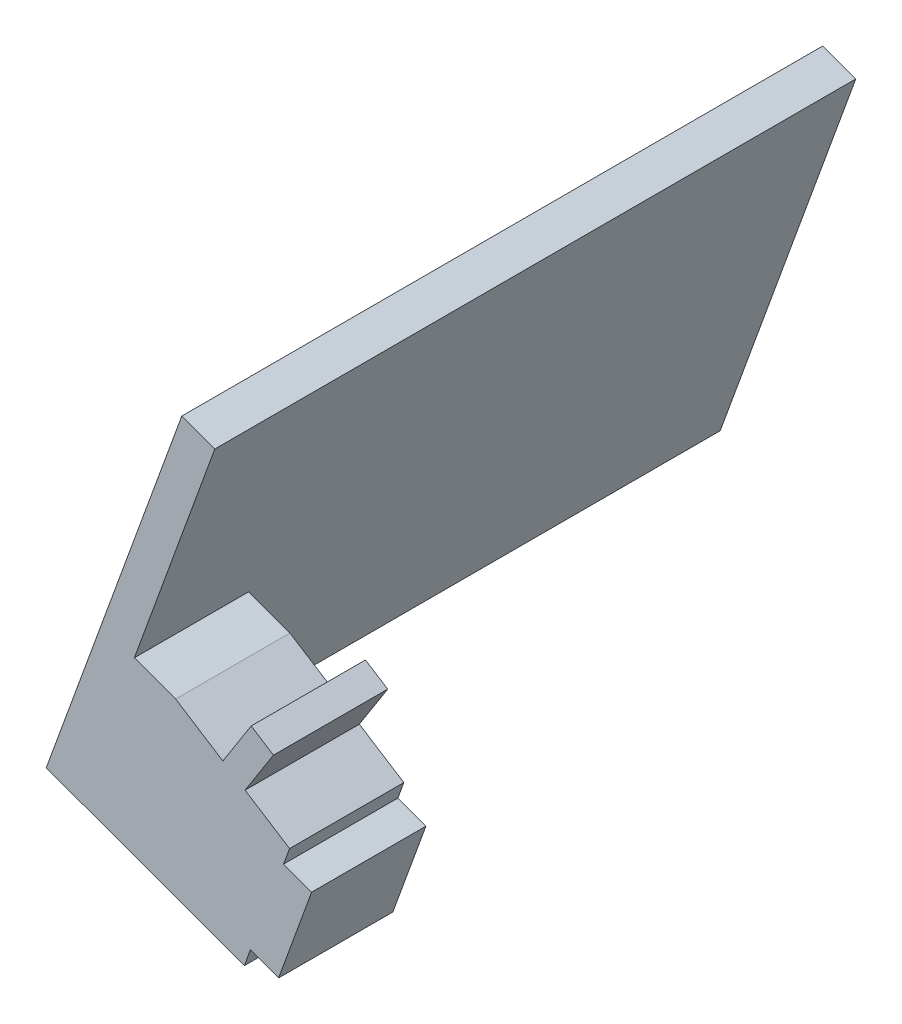
SolidWorks part; units mm, degrees
ref_plane "Plane1" through (0, 0, 0) normal (0, 0, 1) x (1, 0, 0)
ref_plane "Plane2" through (0, 0, 0) normal (0, 1, 0) x (1, 0, 0)
ref_plane "Plane3" through (0, 0, 0) normal (1, 0, 0) x (0, 0, -1)
sketch "Sketch1" plane through (0, 0, 0) normal (0, 0, 1) x (1, 0, 0)
  line L1 (0, 0) -> (203.2, 0)
  line L2 (0, 0) -> (0, 101.6)
  line L3 (0, 101.6) -> (203.2, 101.6)
  line L4 (203.2, 0) -> (203.2, 101.6)
  dimension "D1" = 203.2
  dimension "D2" = 101.6
extrude "Extrude1" add sketch "Sketch1" along normal blind 50.8
sketch "Sketch2" plane through (0, 0, 50.8) normal (0, 0, 1) x (1, 0, 0)
  line L0 (83.0232, 99.06) -> (89.3732, 99.06)
  line L2 (157.48, 83.82) -> (157.48, 78.74)
  line L3 (157.48, 78.74) -> (91.44, 78.74)
  line L4 (91.44, 78.74) -> (83.0232, 99.06)
  line L5 (203.2, 101.6) -> (0, 101.6) construction
  line L6 (0, 101.6) -> (0, 0) construction
  line L7 (157.48, 83.82) -> (102.4931, 88.7077)
  line L8 (98.7377, 90.3765) -> (89.3732, 99.06)
  arc A0 (98.7377, 90.3765) -> (102.4931, 88.7077) centre (103.0553, 95.0328) ccw
  point P12 (100.33, 88.9)
  dimension "D10" = 6.35
  dimension "D1" = 67.5
  dimension "D2" = 20.32
  dimension "D3" = 2.54
  dimension "D4" = 5.08
  dimension "D5" = 66.04
  dimension "D6" = 157.48
  dimension "D7" = 6.35
  dimension "D8" = 57.15
  dimension "D9" = 5.08
sketch "Sketch4" plane through (0, 0, 50.8) normal (0, 0, 1) x (1, 0, 0)
  line L0 (86.5799, 90.4733) -> (72.5, 84.6412)
  line L1 (91.44, 78.74) -> (83.0232, 99.06) construction
  line L2 (72.5, 84.6412) -> (69.6673, 84.8425)
  line L3 (69.6673, 84.8425) -> (73.0694, 76.6292)
  line L4 (73.0694, 76.6292) -> (74.93, 78.7745)
  line L5 (74.93, 78.7745) -> (89.01, 84.6066)
  line L6 (89.01, 84.6066) -> (91.8426, 84.4053)
  line L7 (91.8426, 84.4053) -> (88.4406, 92.6186)
  line L8 (88.4406, 92.6186) -> (86.5799, 90.4733)
  line L9 (79.54, 87.5572) -> (81.97, 81.6906)
  dimension "D1" = 6.35
  dimension "D2" = 8.89
  dimension "D3" = 1.27
  dimension "D4" = 8.89
  dimension "D5" = 1.27
  dimension "D6" = 2.54
  dimension "D7" = 2.54
  dimension "D8" = 15.24
  dimension "D9" = 6.35
sketch "Sketch5" plane through (0, 0, 50.8) normal (0, 0, 1) x (1, 0, 0)
  line L0 (69.7842, 91.1978) -> (77.5603, 72.4245)
  line L1 (77.5603, 72.4245) -> (43.4353, 38.2996)
  line L2 (43.4353, 38.2996) -> (23.4233, 51.0486)
  line L5 (23.4233, 51.0486) -> (30.1436, 56.8684)
  line L6 (157.48, 78.74) -> (91.44, 78.74) construction
  line L7 (30.1436, 56.8684) -> (37.6275, 52.1007)
  line L8 (45.5295, 52.9661) -> (64.4212, 71.8578)
  line L9 (65.7977, 78.778) -> (63.0639, 85.3779)
  line L10 (63.0639, 85.3779) -> (69.7842, 91.1978)
  arc A0 (37.6275, 52.1007) -> (45.5295, 52.9661) centre (41.0393, 57.4562) ccw
  arc A1 (65.7977, 78.778) -> (64.4212, 71.8578) centre (59.9311, 76.3479) cw
  point P14 (41.9258, 49.3624)
  dimension "D10" = 6.35
  dimension "D1" = 135
  dimension "D2" = 6.35
  dimension "D3" = 8.89
  dimension "D4" = 48.26
  dimension "D5" = 102.5
  dimension "D6" = 8.89
  dimension "D7" = 20.32
  dimension "D8" = 8.89
  dimension "D9" = 13.97
sketch "Sketch6" plane through (0, 0, 50.8) normal (0, 0, 1) x (1, 0, 0)
  line L0 (31.6531, 45.8056) -> (23.4647, 32.9524)
  line L1 (43.4353, 38.2996) -> (23.4233, 51.0486) construction
  line L2 (23.4647, 32.9524) -> (21.0288, 31.4925)
  line L3 (21.0288, 31.4925) -> (26.3844, 28.0807)
  line L4 (26.3844, 28.0807) -> (26.678, 30.9052)
  line L5 (26.678, 30.9052) -> (34.8665, 43.7585)
  line L6 (34.8665, 43.7585) -> (37.3023, 45.2184)
  line L7 (37.3023, 45.2184) -> (31.9468, 48.6302)
  line L8 (30.7722, 37.3319) -> (27.5589, 39.379)
  line L9 (31.9468, 48.6302) -> (31.6531, 45.8056)
  dimension "D1" = 3.81
  dimension "D2" = 6.35
  dimension "D3" = 6.35
  dimension "D4" = 1.27
  dimension "D5" = 1.27
  dimension "D6" = 2.54
  dimension "D7" = 2.54
  dimension "D8" = 15.24
  dimension "D9" = 10.16
sketch "Sketch8" plane through (0, 0, 50.8) normal (0, 0, 1) x (1, 0, 0)
  line L0 (16.648, 37.2951) -> (33.1047, 26.811)
  line L1 (33.1047, 26.811) -> (26.5892, 8.9099)
  line L2 (26.5892, 8.9099) -> (2.721, 17.5972)
  line L3 (16.648, 37.2951) -> (10.6809, 39.4669)
  line L4 (2.721, 17.5972) -> (10.6809, 39.4669)
  line L8 (43.4353, 38.2996) -> (23.4233, 51.0486) construction
  dimension "D1" = 7.62
  dimension "D2" = 102.5
  dimension "D3" = 25.4
  dimension "D4" = 19.05
  dimension "D5" = 6.35
sketch "Sketch14" plane through (0, 0, 50.8) normal (0, 0, 1) x (1, 0, 0)
  line L0 (157.48, 78.74) -> (91.44, 78.74) construction
  line L1 (93.98, 80.772) -> (154.94, 80.772)
  line L2 (93.98, 80.772) -> (93.98, 74.422)
  line L3 (93.98, 74.422) -> (154.94, 74.422)
  line L4 (154.94, 80.772) -> (154.94, 74.422)
  line L5 (157.48, 83.82) -> (157.48, 78.74) construction
  dimension "D1" = 2.032
  dimension "D2" = 2.54
  dimension "D3" = 2.54
  dimension "D4" = 6.35
sketch "Sketch15" plane through (0, 0, 50.8) normal (0, 0, 1) x (1, 0, 0)
  line L0 (43.7945, 41.5325) -> (48.2847, 37.0423)
  line L2 (48.2847, 37.0423) -> (78.8175, 67.5752)
  line L3 (78.8175, 67.5752) -> (74.3274, 72.0653)
  line L4 (74.3274, 72.0653) -> (43.7945, 41.5325)
  line L5 (77.5603, 72.4245) -> (43.4353, 38.2996) construction
  dimension "D1" = 2.032
  dimension "D2" = 2.54
  dimension "D3" = 6.35
  dimension "D4" = 2.54
sketch "Sketch16" plane through (0, 0, 50.8) normal (0, 0, 1) x (1, 0, 0)
  line L0 (25.5485, 11.9917) -> (31.5155, 9.8199)
  line L1 (31.5155, 9.8199) -> (36.2935, 22.9474)
  line L2 (36.2935, 22.9474) -> (30.3265, 25.1192)
  line L3 (30.3265, 25.1192) -> (25.5485, 11.9917)
  line L4 (33.1047, 26.811) -> (26.5892, 8.9099) construction
  dimension "D1" = 2.032
  dimension "D2" = 6.35
  dimension "D3" = 2.54
  dimension "D4" = 2.54
sketch "Sketch19" plane through (0, 0, 50.8) normal (0, 0, 1) x (1, 0, 0)
  line L0 (155.194, 72.39) -> (86.506, 72.39)
  line L1 (86.506, 72.39) -> (45.2314, 31.1154)
  line L2 (45.2314, 31.1154) -> (113.9194, 31.1154)
  line L3 (113.9194, 31.1154) -> (155.194, 72.39)
  line L4 (93.98, 74.422) -> (154.94, 74.422) construction
  line L5 (48.2847, 37.0423) -> (78.8175, 67.5752) construction
  line L7 (43.7945, 41.5325) -> (48.2847, 37.0423) construction
  line L8 (154.94, 80.772) -> (154.94, 74.422) construction
  dimension "D1" = 2.032
  dimension "D2" = 2.032
  dimension "D3" = 6.35
  dimension "D4" = 0.254
sketch "Sketch21" plane through (0, 0, 50.8) normal (0, 0, 1) x (1, 0, 0)
  line L0 (10.6809, 39.4669) -> (16.648, 37.2951)
  line L1 (16.648, 37.2951) -> (23.4647, 32.9524)
  line L2 (23.4647, 32.9524) -> (27.5589, 39.379)
  line L3 (27.5589, 39.379) -> (30.7722, 37.3319)
  line L4 (30.7722, 37.3319) -> (26.678, 30.9052)
  line L5 (26.678, 30.9052) -> (33.1047, 26.811)
  line L6 (33.1047, 26.811) -> (32.239, 24.4326)
  line L7 (32.239, 24.4326) -> (36.2935, 22.9474)
  line L8 (36.2935, 22.9474) -> (31.5155, 9.8199)
  line L9 (31.5155, 9.8199) -> (27.4308, 11.3066)
  line L10 (27.4308, 11.3066) -> (26.5892, 8.9099)
  line L11 (26.5892, 8.9099) -> (2.721, 17.5972)
  line L12 (2.721, 17.5972) -> (10.6809, 39.4669)
extrude "Extrude2" add sketch "Sketch21" along normal blind 16.51
sketch "Sketch23" plane through (0, 0, 0) normal (0, -1, 0) x (1, 0, 0)
  line L0 (0, 50.8) -> (0, 0)
  line L1 (0, 50.8) -> (203.2, 50.8) construction
  line L2 (0, 0) -> (203.2, 0)
  line L3 (203.2, 0) -> (203.2, 50.8)
  line L4 (203.2, 50.8) -> (203.2, 0) construction
  line L5 (203.2, 50.8) -> (0, 50.8)
extrude "Extrude3" cut sketch "Sketch23" against normal blind 508
sketch "Sketch24" plane through (-3.2529, 1.184, 0) normal (-0.9397, 0.342, 0) x (0, 0, 1)
  line L0 (67.31, 17.4666) -> (-25.2953, 17.4666)
  line L1 (67.31, 17.4666) -> (67.31, 74.7216)
  line L2 (67.31, 74.7216) -> (50.8, 74.7216)
  line L3 (-25.2953, 17.4666) -> (-25.2953, 74.7216)
  line L4 (50.8, 17.4666) -> (67.31, 17.4666)
  line L5 (-25.2953, 74.7216) -> (67.31, 74.7216)
  line L6 (50.8, 38.1658) -> (50.8, 53.0446) construction
  line M1 (50.8, 40.7399) -> (50.8, 17.4666)
  line M2 (50.8, 17.4666) -> (67.31, 17.4666)
  line M3 (67.31, 17.4666) -> (67.31, 40.7399)
  line M4 (67.31, 40.7399) -> (50.8, 40.7399)
extrude "Extrude6" add sketch "Sketch24" along normal blind 5.08 contours L5 L3 L0 L1 L2 M1 M4 | M4 M1 M2 M3
sketch "Sketch25" plane through (-3.2529, 1.184, 0) normal (0.9397, -0.342, 0) x (0, 0, -1)
  line L0 (-67.31, 40.7399) -> (-50.8, 40.7399)
  line L1 (-67.31, 40.7399) -> (-50.8, 40.7399)
sketch "Sketch27" plane through (-3.2529, 1.184, 0) normal (0.9397, -0.342, 0) x (0, 0, -1)
  line L0 (-67.31, 46.5049) -> (-50.7484, 46.5049)
  line L1 (-67.31, 40.7399) -> (-67.31, 74.7216) construction
